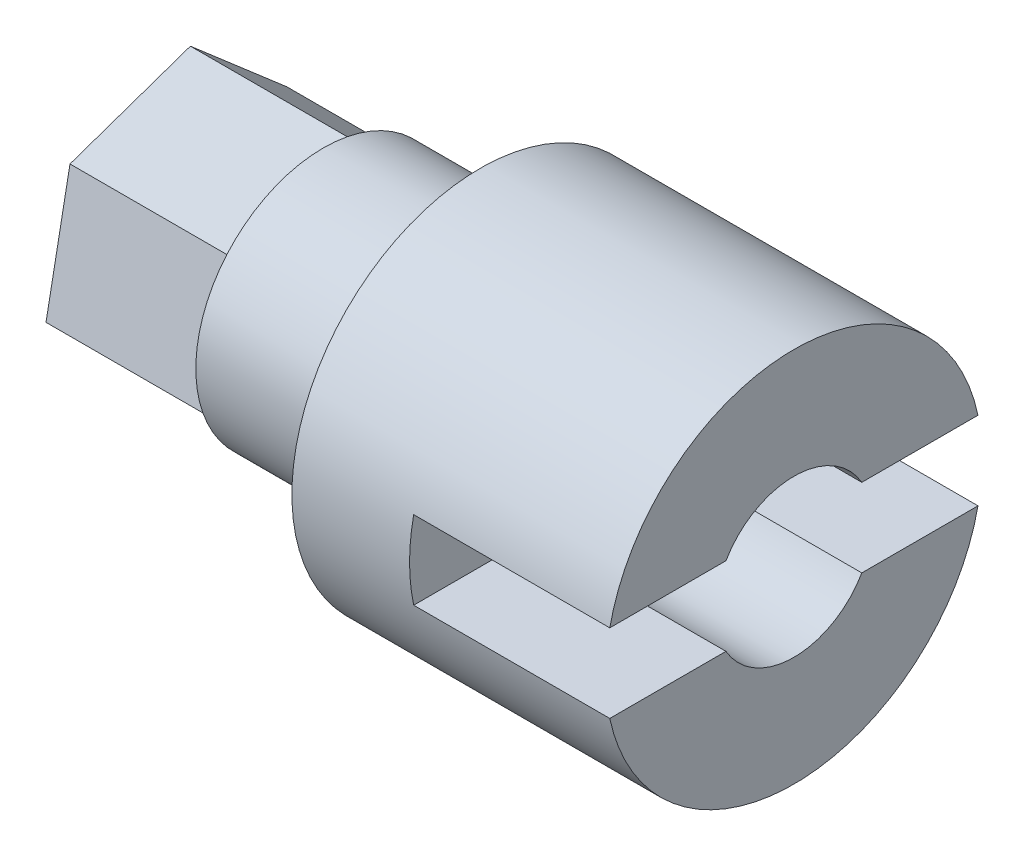
SolidWorks part; units mm, degrees
ref_plane "前视基准面" through (0, 0, 0) normal (0, 0, 1) x (1, 0, 0)
ref_plane "上视基准面" through (0, 0, 0) normal (0, 1, 0) x (1, 0, 0)
ref_plane "右视基准面" through (0, 0, 0) normal (1, 0, 0) x (0, 0, -1)
sketch "草图1" plane through (0, 0, 0) normal (1, 0, 0) x (0, 0, -1)
  circle A0 centre (0, 0) radius 4.8
  circle A1 centre (0, 0) radius 2
  dimension "D1" = 9.6
  dimension "D2" = 4
extrude "凸台-拉伸1" add sketch "草图1" along normal blind 8
sketch "草图2" plane through (8, 0, 0) normal (1, 0, 0) x (0, 0, -1)
  line L1 (-5.9747, 1) -> (6.0253, 1)
  line L2 (-5.9747, 1) -> (-5.9747, -1)
  line L3 (-5.9747, -1) -> (6.0253, -1)
  line L4 (6.0253, 1) -> (6.0253, -1)
  circle A0 centre (0, 0) radius 2 construction
  dimension "D1" = 2
  dimension "D2" = 12
  dimension "D3" = 1
extrude "切除-拉伸1" cut sketch "草图2" against normal blind 5
sketch "草图7" plane through (0, 0, 0) normal (-1, 0, 0) x (0, 0, 1)
  circle A0 centre (0, 0) radius 2
extrude "凸台-拉伸4" add sketch "草图7" against normal blind 2
sketch "草图8" plane through (0, 0, 0) normal (-1, 0, 0) x (0, 0, 1)
  circle A0 centre (0, 0) radius 3.25
  dimension "D1" = 6.5
extrude "凸台-拉伸5" add sketch "草图8" along normal blind 8
sketch "草图9" plane through (-8, 0, 0) normal (-1, 0, 0) x (0, 0, 1)
  circle A0 centre (0, 0) radius 1.35
  dimension "D1" = 2.7
extrude "切除-拉伸3" cut sketch "草图9" against normal through all
sketch "草图10" plane through (-8, 0, 0) normal (-1, 0, 0) x (0, 0, 1)
  line L1 (-3.0701, 1.0663) -> (-2.4585, -2.1256)
  line L2 (-2.4585, -2.1256) -> (0.6116, -3.1919)
  line L3 (0.6116, -3.1919) -> (3.0701, -1.0663)
  line L4 (3.0701, -1.0663) -> (2.4585, 2.1256)
  line L5 (2.4585, 2.1256) -> (-0.6116, 3.1919)
  line L6 (-0.6116, 3.1919) -> (-3.0701, 1.0663)
  circle A0 centre (0, 0) radius 2.8146 construction
extrude "切除-拉伸4" cut sketch "草图10" against normal blind 4 flip side to cut
